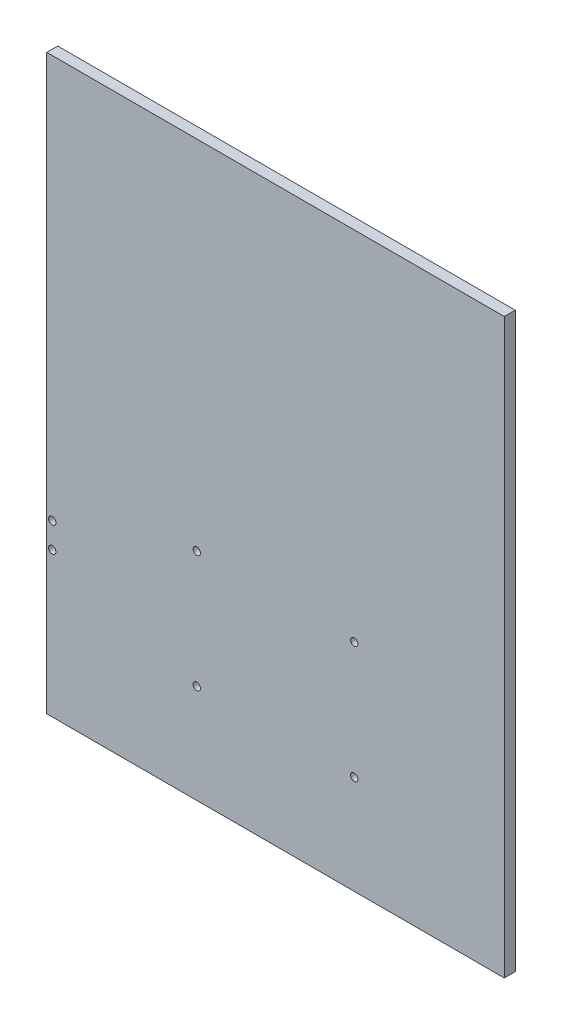
SolidWorks part; units mm, degrees
ref_plane "Plan de face" through (0, 0, 0) normal (0, 0, 1) x (1, 0, 0)
ref_plane "Plan de dessus" through (0, 0, 0) normal (0, 1, 0) x (1, 0, 0)
ref_plane "Plan de droite" through (0, 0, 0) normal (1, 0, 0) x (0, 0, -1)
sketch "Esquisse1" plane through (0, 0, 0) normal (0, 0, 1) x (1, 0, 0)
  line L0 (-150, 0) -> (-150, 141) construction
  line L1 (-200, 141) -> (50, 141)
  line L2 (-200, 141) -> (-200, -172)
  line L3 (-200, -172) -> (50, -172)
  line L4 (50, 141) -> (50, -172)
  line L5 (0, 141) -> (0, 0) construction
  line L6 (-121.5, -122) -> (-28.5, -122) construction
  line L7 (-150, 141) -> (0, 141) construction
  dimension "D1" = 50
  dimension "D2" = 50
  dimension "D3" = 50
extrude "Boss.-Extru.1" add sketch "Esquisse1" along normal blind 6
sketch "Esquisse2" plane through (0, 0, 0) normal (0, 0, -1) x (-1, 0, 0)
  circle A0 centre (32, -54) radius 2
  circle A1 centre (118, -54) radius 2
  circle A2 centre (118, -118) radius 2
  circle A3 centre (32, -118) radius 2
  dimension "D1" = 4
extrude "Enlèv. mat.-Extru.1" cut sketch "Esquisse2" against normal up to next
sketch "Esquisse3" plane through (0, 0, 0) normal (0, 0, -1) x (-1, 0, 0)
  circle A0 centre (197, -79.1) radius 2
  circle A1 centre (197, -92.9) radius 2
  dimension "D1" = 4
extrude "Enlèv. mat.-Extru.2" cut sketch "Esquisse3" against normal up to next
